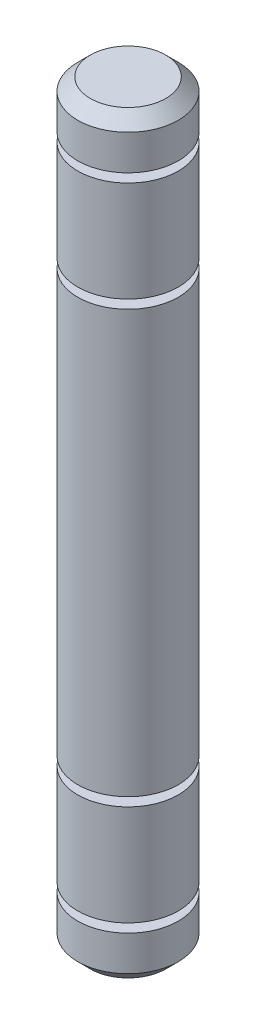
SolidWorks part; units mm, degrees
material "AISI 1045 Steel, cold drawn"
ref_plane "Front Plane" through (0, 0, 0) normal (0, 0, 1) x (1, 0, 0)
ref_plane "Top Plane" through (0, 0, 0) normal (0, 1, 0) x (1, 0, 0)
ref_plane "Right Plane" through (0, 0, 0) normal (1, 0, 0) x (0, 0, -1)
sketch "Sketch1" plane through (0, 0, 0) normal (0, 0, 1) x (1, 0, 0)
  line L0 (4, 0) -> (4, 3.8)
  line L4 (4, 4.5) -> (4, 12.5)
  line L8 (4, 13.2) -> (4, 46.8)
  line L9 (-10.8799, 30) -> (21.7453, 30) construction
  line L16 (4, 56.2) -> (4, 60)
  line L17 (4, 47.5) -> (4, 55.5)
  line L23 (4, 4.5) -> (2.9, 4.5)
  line L24 (2.7, 4.3) -> (2.7, 4)
  line L25 (2.9, 3.8) -> (4, 3.8)
  line L26 (4, 13.2) -> (2.9, 13.2)
  line L27 (2.7, 13) -> (2.7, 12.7)
  line L28 (2.9, 12.5) -> (4, 12.5)
  line L29 (2.7, 47) -> (2.7, 47.3)
  line L30 (2.9, 47.5) -> (4, 47.5)
  line L31 (4, 46.8) -> (2.9, 46.8)
  line L32 (2.9, 56.2) -> (4, 56.2)
  line L33 (2.7, 55.7) -> (2.7, 56)
  line L34 (4, 55.5) -> (2.9, 55.5)
  line L35 (4, 0) -> (0, 0)
  line L36 (0, 0) -> (0, 60)
  line L37 (0, 60) -> (4, 60)
  arc A0 (2.7, 47) -> (2.9, 46.8) centre (2.9, 47) ccw
  arc A1 (2.7, 47.3) -> (2.9, 47.5) centre (2.9, 47.3) cw
  arc A2 (2.7, 55.7) -> (2.9, 55.5) centre (2.9, 55.7) ccw
  arc A3 (2.9, 56.2) -> (2.7, 56) centre (2.9, 56) ccw
  arc A4 (2.7, 4) -> (2.9, 3.8) centre (2.9, 4) ccw
  arc A5 (2.9, 4.5) -> (2.7, 4.3) centre (2.9, 4.3) ccw
  arc A6 (2.7, 12.7) -> (2.9, 12.5) centre (2.9, 12.7) ccw
  arc A7 (2.9, 13.2) -> (2.7, 13) centre (2.9, 13) ccw
  point P24 (2.7, 46.8)
  point P28 (2.7, 47.5)
  point P31 (2.7, 55.5)
  point P34 (2.7, 56.2)
  point P37 (2.7, 3.8)
  point P40 (2.7, 4.5)
  point P43 (2.7, 12.5)
  point P46 (2.7, 13.2)
  dimension "D8" = 0.2
  dimension "D9" = 0.2
  dimension "D1" = 60
  dimension "D2" = 8
  dimension "D3" = 3.8
  dimension "D4" = 1.3
  dimension "D5" = 0.7
  dimension "D6" = 30
  dimension "D7" = 4
revolve "Revolve2" add sketch "Sketch1" angle 360 about L36
chamfer "Chamfer1" distance 1 angle 45 2 edges at (4, 0, 0) (4, 60, 0)
